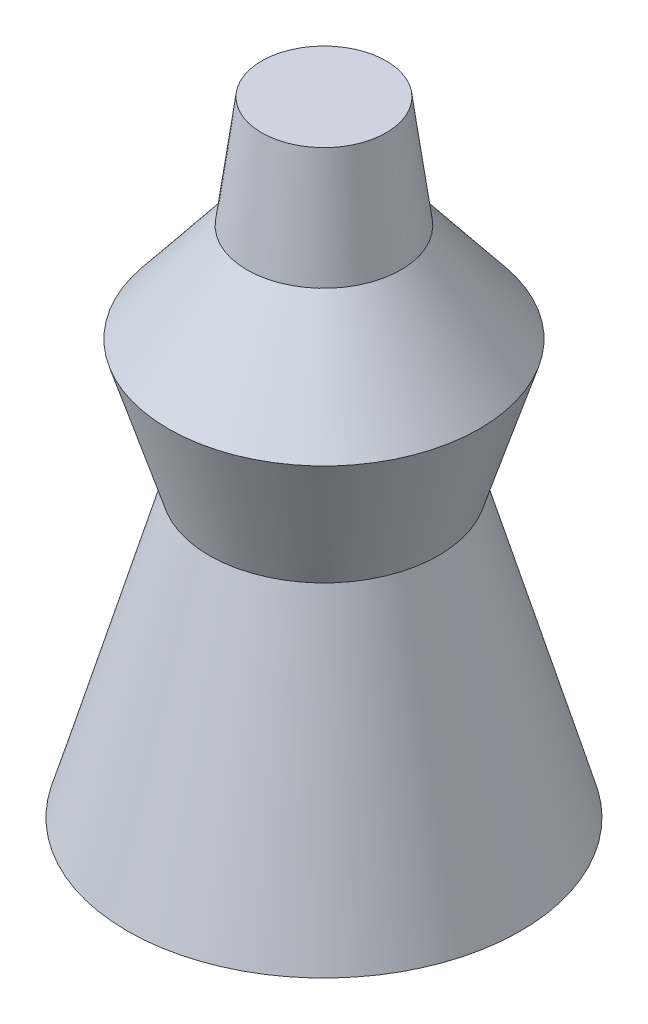
SolidWorks part; units mm, degrees
ref_plane "Front Plane" through (0, 0, 0) normal (0, 0, 1) x (1, 0, 0)
ref_plane "Top Plane" through (0, 0, 0) normal (0, 1, 0) x (1, 0, 0)
ref_plane "Right Plane" through (0, 0, 0) normal (1, 0, 0) x (0, 0, -1)
sketch "Sketch1" plane through (0, 0, 0) normal (0, 0, 1) x (1, 0, 0)
  line L0 (0, 47.0146) -> (0, -39.311)
  line L1 (0, -39.311) -> (27.1892, -39.311)
  line L2 (27.1892, -39.311) -> (15.8603, 0)
  line L3 (15.8603, 0) -> (21.5248, 18.0128)
  line L4 (21.5248, 18.0128) -> (10.6491, 31.6074)
  line L5 (10.6491, 31.6074) -> (8.6099, 47.0146)
  line L6 (8.6099, 47.0146) -> (0, 47.0146)
revolve "Revolve1" add sketch "Sketch1" angle 360 about L0
